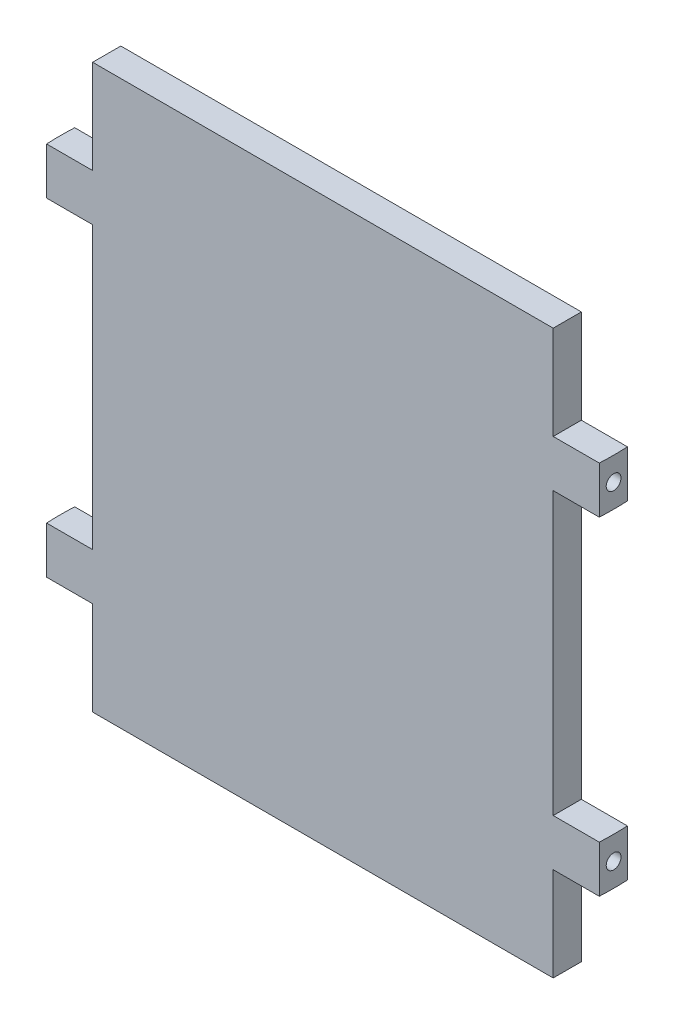
SolidWorks part; units mm, degrees
ref_plane "Ön Düzlem" through (0, 0, 0) normal (0, 0, 1) x (1, 0, 0)
ref_plane "Üst Düzlem" through (0, 0, 0) normal (0, 1, 0) x (1, 0, 0)
ref_plane "Sağ Düzlem" through (0, 0, 0) normal (1, 0, 0) x (0, 0, -1)
sketch "Çizim1" plane through (0, 0, 0) normal (0, 0, 1) x (1, 0, 0)
  line L0 (0, 20) -> (-10, 20)
  line L1 (0, 0) -> (98.2, 0)
  line L2 (0, 0) -> (0, 20)
  line L3 (0, 120) -> (98.2, 120)
  line L4 (98.2, 0) -> (98.2, 20)
  line L5 (-10, 20) -> (-10, 30)
  line L6 (-10, 30) -> (0, 30)
  line L7 (0, 90) -> (-10, 90)
  line L8 (-10, 90) -> (-10, 100)
  line L9 (-10, 100) -> (0, 100)
  line L10 (49.1, 120) -> (49.1, 0) construction
  line L11 (98.2, 20) -> (108.2, 20)
  line L12 (108.2, 20) -> (108.2, 30)
  line L13 (108.2, 30) -> (98.2, 30)
  line L14 (108.2, 100) -> (98.2, 100)
  line L15 (108.2, 90) -> (108.2, 100)
  line L16 (98.2, 90) -> (108.2, 90)
  line L17 (0, 100) -> (0, 120)
  line L18 (0, 30) -> (0, 90)
  line L19 (98.2, 30) -> (98.2, 90)
  line L20 (98.2, 100) -> (98.2, 120)
  dimension "D1" = 98.2
  dimension "D2" = 120
  dimension "D3" = 10
  dimension "D4" = 10
  dimension "D5" = 20
  dimension "D6" = 20
extrude "Yükseklik-Ekstrüzyon1" add sketch "Çizim1" along normal blind 6
sketch "Çizim3" plane through (-10, 0, 0) normal (-1, 0, 0) x (0, 0, 1)
  line L0 (3, 20) -> (3, 25) construction
  line L1 (6, 20) -> (0, 20) construction
  line L2 (3, 100) -> (3, 95) construction
  line L3 (6, 100) -> (0, 100) construction
  point P1 (3, 25)
  point P5 (3, 95)
  point P11 (3, 95)
  point P15 (3, 25)
  dimension "D1" = 5
  dimension "D2" = 5
hole_wizard "M3x0.5 Helisarmal İçin Dişli Delik1" positions "Çizim3" profile "Çizim4" tap size "M3x0.5" standard "Helicoil® Metric"
sketch "Çizim4" plane through (-10, 25, 3) normal (0, 1, 0) x (0, 0, 1)
  line L0 (0, 0) -> (0, 8.4464)
  line L1 (0, 8.4464) -> (1.575, 7.5)
  line L2 (1.575, 7.5) -> (1.575, 0)
  line L5 (1.575, 0) -> (0, 0)
  line L10 (0, 8.4464) -> (-1.575, 7.5) construction
  line L11 (0, -6.35) -> (0, 107.95) construction
  dimension "Tap Drill Dia." = 3.15
  dimension "Tap Drill Depth" = 7.5
  dimension "Drill Angle" = 118
cosmetic thread "Delik Dişi1" parameters "D1"=3.5, "D2"=3.716
cosmetic thread "Delik Dişi2" parameters "D1"=3.5, "D2"=3.716
sketch "Çizim7" plane through (108.2, 0, 0) normal (1, 0, 0) x (0, 0, -1)
  line L0 (-3, 100) -> (-3, 95) construction
  line L1 (-6, 100) -> (0, 100) construction
  line L2 (-3, 20) -> (-3, 25) construction
  line L3 (-6, 20) -> (0, 20) construction
  point P1 (-3, 95)
  point P5 (-3, 25)
  point P12 (-3, 95)
  point P16 (-3, 25)
  dimension "D1" = 5
  dimension "D2" = 5
hole_wizard "M3x0.5 Helisarmal İçin Dişli Delik2" positions "Çizim7" profile "Çizim8" tap size "M3x0.5" standard "Helicoil® Metric"
sketch "Çizim8" plane through (108.2, 25, 3) normal (0, 1, 0) x (0, 0, -1)
  line L0 (0, 0) -> (0, 8.4464)
  line L1 (0, 8.4464) -> (1.575, 7.5)
  line L2 (1.575, 7.5) -> (1.575, 0)
  line L5 (1.575, 0) -> (0, 0)
  line L10 (0, 8.4464) -> (-1.575, 7.5) construction
  line L11 (0, -6.35) -> (0, 107.95) construction
  dimension "Tap Drill Dia." = 3.15
  dimension "Tap Drill Depth" = 7.5
  dimension "Drill Angle" = 118
cosmetic thread "Delik Dişi3" parameters "D1"=3.5, "D2"=3.716
cosmetic thread "Delik Dişi4" parameters "D1"=3.5, "D2"=3.716
sketch "Çizim2" plane through (0, 120, 0) normal (0, 1, 0) x (1, 0, 0)
  line L0 (49.1, -6) -> (49.1, -3) construction
  line L1 (98.2, -6) -> (0, -6) construction
  circle A0 centre (49.1, -3) radius 59
  dimension "D2" = 118
  dimension "D1" = 3
extrude "Kes-Ekstrüzyon-İnce1" cut sketch "Çizim2" against normal blind 150 thin
